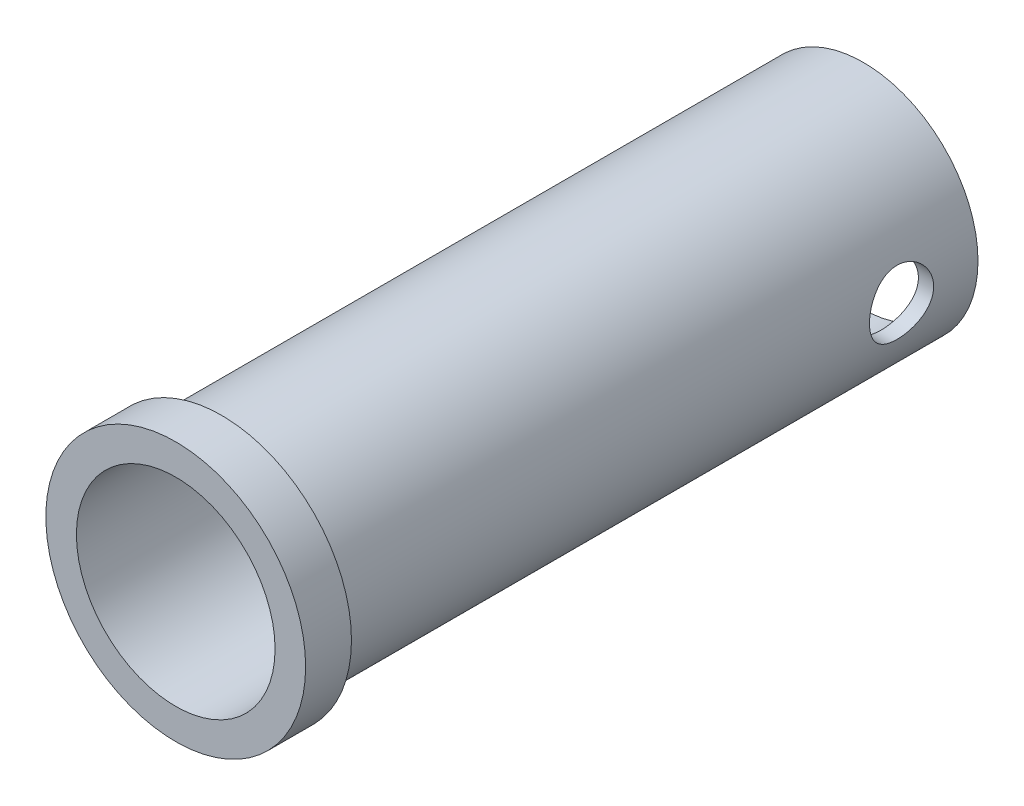
SolidWorks part; units mm, degrees
material "Gerais  - 6061-T6"
ref_plane "Plano frontal" through (0, 0, 0) normal (0, 0, 1) x (1, 0, 0)
ref_plane "Plano superior" through (0, 0, 0) normal (0, 1, 0) x (1, 0, 0)
ref_plane "Plano direito" through (0, 0, 0) normal (1, 0, 0) x (0, 0, -1)
sketch "Esboço1" plane through (0, 0, 0) normal (0, 0, 1) x (1, 0, 0)
  circle A0 centre (0, 0) radius 6.5
  circle A1 centre (0, 0) radius 8.5
  dimension "D1" = 17
  dimension "D2" = 13
extrude "Ressalto-extrusão1" add sketch "Esboço1" along normal blind 3
sketch "Esboço3" plane through (0, 0, 0) normal (0, 0, -1) x (-1, 0, 0)
  circle A0 centre (0, 0) radius 7.5
  circle A1 centre (0, 0) radius 6.5 construction
  circle A2 centre (0, 0) radius 6.5
  dimension "D1" = 15
extrude "Ressalto-extrusão3" add sketch "Esboço3" along normal blind 42
sketch "Esboço4" plane through (0, 0, 0) normal (1, 0, 0) x (0, 0, -1)
  line L0 (42, -7.5) -> (42, 7.5) construction
  circle A0 centre (37, 0) radius 2.1
  point P4 (42, 0)
  dimension "D2" = 4.2
  dimension "D1" = 5
extrude "Corte-extrusão1" cut sketch "Esboço4" against normal through all both and the other way through all
